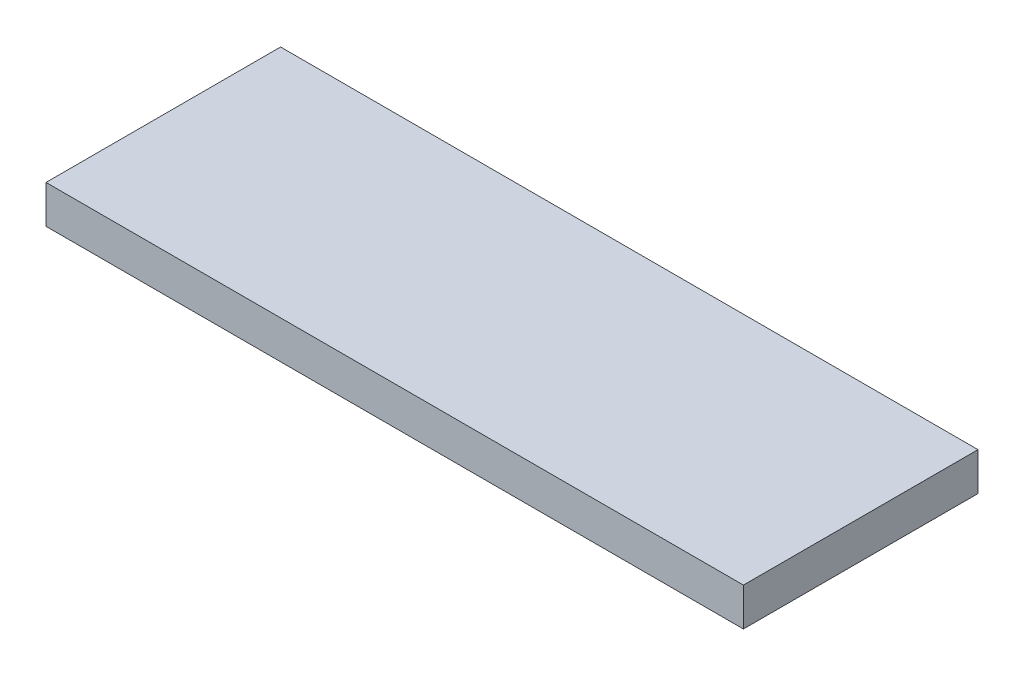
SolidWorks part; units mm, degrees
material "Acrylic (Medium-high impact)"
ref_plane "Front Plane" through (0, 0, 0) normal (0, 0, 1) x (1, 0, 0)
ref_plane "Top Plane" through (0, 0, 0) normal (0, 1, 0) x (1, 0, 0)
ref_plane "Right Plane" through (0, 0, 0) normal (1, 0, 0) x (0, 0, -1)
sketch "Sketch1" plane through (0, 0, 0) normal (0, 1, 0) x (1, 0, 0)
  line L1 (-95.7391, 30.1304) -> (14.2609, 30.1304)
  line L2 (-95.7391, 30.1304) -> (-95.7391, -6.8696)
  line L3 (-95.7391, -6.8696) -> (14.2609, -6.8696)
  line L4 (14.2609, 30.1304) -> (14.2609, -6.8696)
  dimension "D1" = 37
  dimension "D2" = 110
extrude "Boss-Extrude1" add sketch "Sketch1" along normal blind 6
